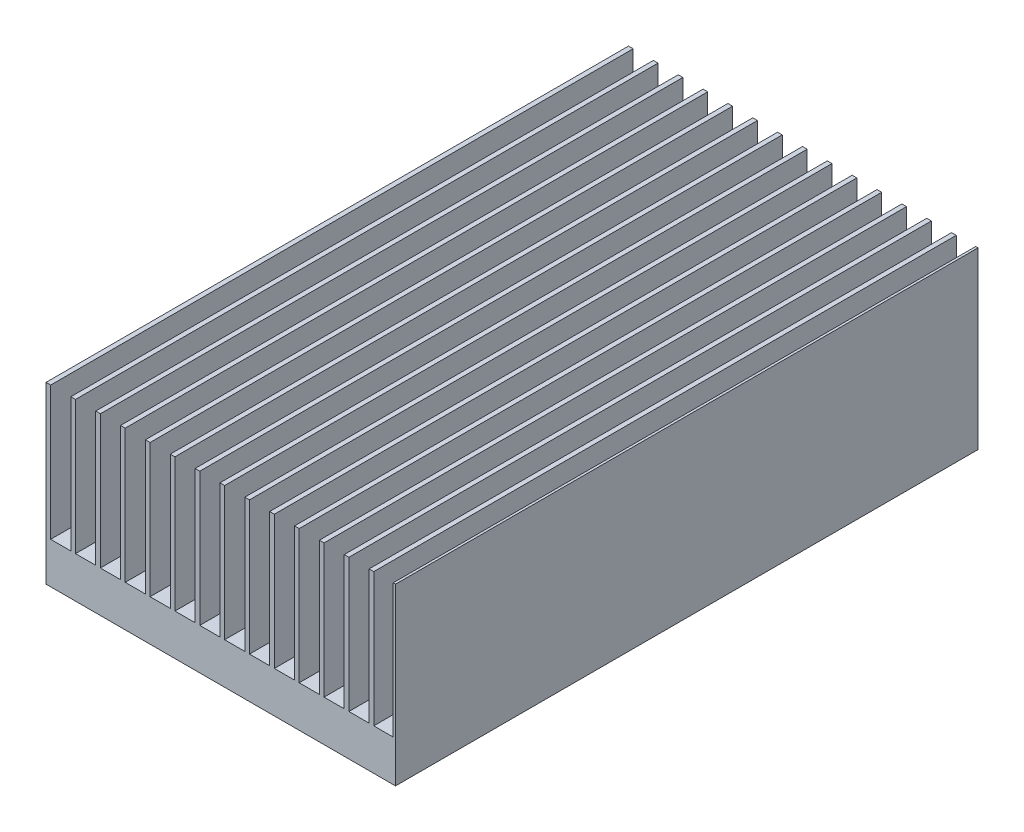
SolidWorks part; units mm, degrees
material "6061-T6 (SS)"
ref_plane "Front Plane" through (0, 0, 0) normal (0, 0, 1) x (1, 0, 0)
ref_plane "Top Plane" through (0, 0, 0) normal (0, 1, 0) x (1, 0, 0)
ref_plane "Right Plane" through (0, 0, 0) normal (1, 0, 0) x (0, 0, -1)
sketch "Sketch1" plane through (0, 0, 0) normal (0, 0, 1) x (1, 0, 0)
  line L0 (41.91, 6.731) -> (48.514, 6.731)
  line L1 (-57.15, -6.731) -> (57.15, -6.731)
  line L2 (-57.15, -6.731) -> (-57.15, 6.731)
  line L3 (-55.626, 6.731) -> (-49.022, 6.731)
  line L4 (57.15, -6.731) -> (57.15, 6.731)
  line L5 (-57.15, -6.731) -> (57.15, 6.731) construction
  line L6 (-57.15, 6.731) -> (57.15, -6.731) construction
  line L7 (50.038, 6.731) -> (56.388, 6.731)
  line L8 (57.15, 6.731) -> (57.15, 50.419)
  line L9 (57.15, 50.419) -> (56.388, 50.419)
  line L10 (56.388, 6.731) -> (56.388, 50.419)
  line L11 (33.782, 6.731) -> (40.386, 6.731)
  line L12 (50.038, 6.731) -> (50.038, 50.419)
  line L13 (50.038, 50.419) -> (48.514, 50.419)
  line L14 (48.514, 6.731) -> (48.514, 50.419)
  line L15 (41.91, 6.731) -> (41.91, 50.419)
  line L16 (41.91, 50.419) -> (40.386, 50.419)
  line L17 (40.386, 6.731) -> (40.386, 50.419)
  line L18 (25.654, 6.731) -> (32.258, 6.731)
  line L19 (33.782, 6.731) -> (33.782, 50.419)
  line L20 (33.782, 50.419) -> (32.258, 50.419)
  line L21 (32.258, 6.731) -> (32.258, 50.419)
  line L22 (17.526, 6.731) -> (24.13, 6.731)
  line L23 (25.654, 6.731) -> (25.654, 50.419)
  line L24 (25.654, 50.419) -> (24.13, 50.419)
  line L25 (24.13, 6.731) -> (24.13, 50.419)
  line L26 (9.398, 6.731) -> (16.002, 6.731)
  line L27 (17.526, 6.731) -> (17.526, 50.419)
  line L28 (17.526, 50.419) -> (16.002, 50.419)
  line L29 (16.002, 6.731) -> (16.002, 50.419)
  line L30 (1.27, 6.731) -> (7.874, 6.731)
  line L31 (9.398, 6.731) -> (9.398, 50.419)
  line L32 (9.398, 50.419) -> (7.874, 50.419)
  line L33 (7.874, 6.731) -> (7.874, 50.419)
  line L34 (-6.858, 6.731) -> (-0.254, 6.731)
  line L35 (1.27, 6.731) -> (1.27, 50.419)
  line L36 (1.27, 50.419) -> (-0.254, 50.419)
  line L37 (-0.254, 6.731) -> (-0.254, 50.419)
  line L39 (-6.858, 6.731) -> (-6.858, 50.419)
  line L40 (-6.858, 50.419) -> (-8.382, 50.419)
  line L41 (-8.382, 6.731) -> (-8.382, 50.419)
  line L42 (-14.986, 6.731) -> (-8.382, 6.731)
  line L43 (-14.986, 6.731) -> (-14.986, 50.419)
  line L44 (-14.986, 50.419) -> (-16.51, 50.419)
  line L45 (-16.51, 6.731) -> (-16.51, 50.419)
  line L46 (-23.114, 6.731) -> (-16.51, 6.731)
  line L47 (-23.114, 6.731) -> (-23.114, 50.419)
  line L48 (-23.114, 50.419) -> (-24.638, 50.419)
  line L49 (-24.638, 6.731) -> (-24.638, 50.419)
  line L50 (-31.242, 6.731) -> (-24.638, 6.731)
  line L51 (-31.242, 6.731) -> (-31.242, 50.419)
  line L52 (-31.242, 50.419) -> (-32.766, 50.419)
  line L53 (-32.766, 6.731) -> (-32.766, 50.419)
  line L54 (-39.37, 6.731) -> (-32.766, 6.731)
  line L55 (-39.37, 6.731) -> (-39.37, 50.419)
  line L56 (-39.37, 50.419) -> (-40.894, 50.419)
  line L57 (-40.894, 6.731) -> (-40.894, 50.419)
  line L59 (-47.498, 6.731) -> (-47.498, 50.419)
  line L60 (-47.498, 50.419) -> (-49.022, 50.419)
  line L61 (-49.022, 6.731) -> (-49.022, 50.419)
  line L62 (-47.498, 6.731) -> (-40.894, 6.731)
  line L63 (-55.626, 6.731) -> (-55.626, 50.419)
  line L64 (-55.626, 50.419) -> (-57.15, 50.419)
  line L65 (-57.15, 6.731) -> (-57.15, 50.419)
  line L188 (-55.626, 6.731) -> (-57.15, 6.731) [skipped]
  line L189 (-47.498, 6.731) -> (-49.022, 6.731) [skipped]
  line L190 (-39.37, 6.731) -> (-40.894, 6.731) [skipped]
  line L191 (-31.242, 6.731) -> (-32.766, 6.731) [skipped]
  line L192 (-23.114, 6.731) -> (-24.638, 6.731) [skipped]
  line L193 (-14.986, 6.731) -> (-16.51, 6.731) [skipped]
  line L194 (50.038, 6.731) -> (48.514, 6.731) [skipped]
  line L195 (41.91, 6.731) -> (40.386, 6.731) [skipped]
  line L196 (33.782, 6.731) -> (32.258, 6.731) [skipped]
  line L197 (25.654, 6.731) -> (24.13, 6.731) [skipped]
  line L198 (17.526, 6.731) -> (16.002, 6.731) [skipped]
  line L199 (9.398, 6.731) -> (7.874, 6.731) [skipped]
  line L200 (1.27, 6.731) -> (-0.254, 6.731) [skipped]
  line L201 (-6.858, 6.731) -> (-8.382, 6.731) [skipped]
  point P0 (0, 0)
  dimension "D1" = 114.3
  dimension "D2" = 0.762
  dimension "D3" = 43.688
  dimension "D4" = 57.15
  dimension "D5" = 6.35
  dimension "D6" = 1.524
  dimension "D7" = 14
extrude "Boss-Extrude1" add sketch "Sketch1" along normal mid plane 190.5
hole_wizard "#8-32 Tapped Hole1" positions "Sketch4" profile "Sketch3" tap size "#8-32" standard "Ansi Inch"
sketch "Sketch4" plane through (0, -6.731, 0) normal (0, -1, 0) x (1, 0, 0)
  line L0 (-57.15, 95.25) -> (57.15, 95.25) construction
  line L1 (57.15, 95.25) -> (57.15, -95.25) construction
  point P0 (47.625, 85.725)
  dimension "D1" = 9.525
  dimension "D2" = 9.525
sketch "Sketch3" plane through (47.625, -6.731, 85.725) normal (1, 0, 0) x (0, 0, -1)
  line L0 (0, 0) -> (0, 12.9758)
  line L1 (0, 12.9758) -> (1.7272, 11.938)
  line L2 (1.7272, 11.938) -> (1.7272, 0)
  line L5 (1.7272, 0) -> (0, 0)
  line L10 (0, 12.9758) -> (-1.7272, 11.938) construction
  line L11 (0, -6.35) -> (0, 107.95) construction
  dimension "Tap Drill Dia." = 3.4544
  dimension "Tap Drill Depth" = 11.938
  dimension "Drill Angle" = 118
cosmetic thread "Hole Thread1" parameters "D1"=9.652, "D2"=4.1656
hole_wizard "#4-40 Tapped Hole1" positions "Sketch6" profile "Sketch5" tap size "#4-40" standard "Ansi Inch"
sketch "Sketch6" plane through (0, -6.731, 0) normal (0, -1, 0) x (1, 0, 0)
  line L0 (-57.15, 95.25) -> (57.15, 95.25) construction
  line L1 (57.15, 95.25) -> (57.15, -95.25) construction
  point P0 (38.989, 25.908)
  dimension "D1" = 69.342
  dimension "D2" = 18.161
sketch "Sketch5" plane through (38.989, -6.731, 25.908) normal (1, 0, 0) x (0, 0, -1)
  line L0 (0, 0) -> (0, 11.8552)
  line L1 (0, 11.8552) -> (1.1303, 11.176)
  line L2 (1.1303, 11.176) -> (1.1303, 0)
  line L5 (1.1303, 0) -> (0, 0)
  line L10 (0, 11.8552) -> (-1.1303, 11.176) construction
  line L11 (0, -6.35) -> (0, 107.95) construction
  dimension "Tap Drill Dia." = 2.2606
  dimension "Tap Drill Depth" = 11.176
  dimension "Drill Angle" = 118
cosmetic thread "Hole Thread2" parameters "D1"=7.874, "D2"=2.8448
pattern_linear "LPattern1" count 2 spacing 171.45 along (0, 0, -1) of "#8-32 Tapped Hole1"
pattern_linear "LPattern2" count 2 spacing 103.378 along (0, 0, -1) of "#4-40 Tapped Hole1"
mirror "Mirror1" about plane through (0, 0, 0) normal (1, 0, 0) of "LPattern1", "LPattern2", "#8-32 Tapped Hole1", "#4-40 Tapped Hole1"
